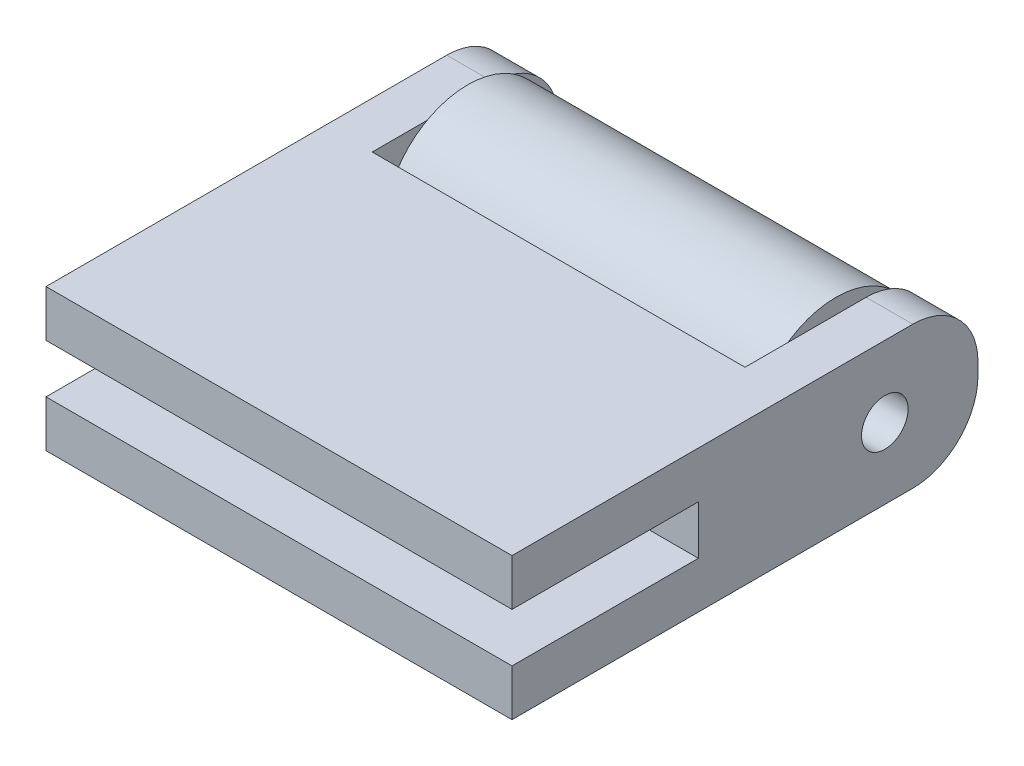
SolidWorks part; units mm, degrees
ref_plane "Front Plane" through (0, 0, 0) normal (0, 0, 1) x (1, 0, 0)
ref_plane "Top Plane" through (0, 0, 0) normal (0, 1, 0) x (1, 0, 0)
ref_plane "Right Plane" through (0, 0, 0) normal (1, 0, 0) x (0, 0, -1)
sketch "Sketch1" plane through (0, 0, 0) normal (1, 0, 0) x (0, 0, -1)
  line L1 (0, 0) -> (50, 0)
  line L2 (0, 0) -> (0, 15.25)
  line L3 (0, 15.25) -> (50, 15.25)
  line L4 (50, 0) -> (50, 15.25)
  line L5 (0, 10.25) -> (20, 10.25)
  line L6 (0, 10.25) -> (0, 5)
  line L7 (0, 5) -> (20, 5)
  line L8 (20, 10.25) -> (20, 5)
  circle A0 centre (40, 7.625) radius 2.5
  dimension "D6" = 5
  dimension "D1" = 5
  dimension "D2" = 5
  dimension "D3" = 5.25
  dimension "D4" = 20
  dimension "D5" = 30
  dimension "D7" = 7.625
  dimension "D8" = 10
extrude "Boss-Extrude1" add sketch "Sketch1" along normal blind 50 contours L5 L8 L7 L2 L1 L4 L3
sketch "Sketch2" plane through (0, 15.25, 0) normal (0, 1, 0) x (1, 0, 0)
  line L0 (50, 50) -> (0, 50) construction
  line L1 (5, 50) -> (45, 50)
  line L2 (5, 50) -> (5, 30)
  line L3 (5, 30) -> (45, 30)
  line L4 (45, 50) -> (45, 30)
  line L5 (0, 0) -> (0, 50) construction
  line L6 (50, 0) -> (50, 50) construction
  dimension "D1" = 5
  dimension "D2" = 5
  dimension "D3" = 20
extrude "Cut-Extrude1" cut sketch "Sketch2" against normal through all
fillet "Fillet1" radius 7 4 edges at (47.5, 0, -50) (2.5, 0, -50) (2.5, 15.25, -50) (47.5, 15.25, -50)
sketch "Sketch3" plane through (5, 0, 0) normal (1, 0, 0) x (0, 0, -1)
  circle A0 centre (40, 7.625) radius 9
  dimension "D1" = 18
extrude "Boss-Extrude2" add sketch "Sketch3" along normal blind 39.5 from offset 0.25 separate body
sketch "Sketch4" plane through (5.25, 0, 0) normal (-1, 0, 0) x (0, 0, 1)
  circle A0 centre (-40, 7.625) radius 2.375
  dimension "D1" = 4.75
extrude "Cut-Extrude2" cut sketch "Sketch4" against normal through all
